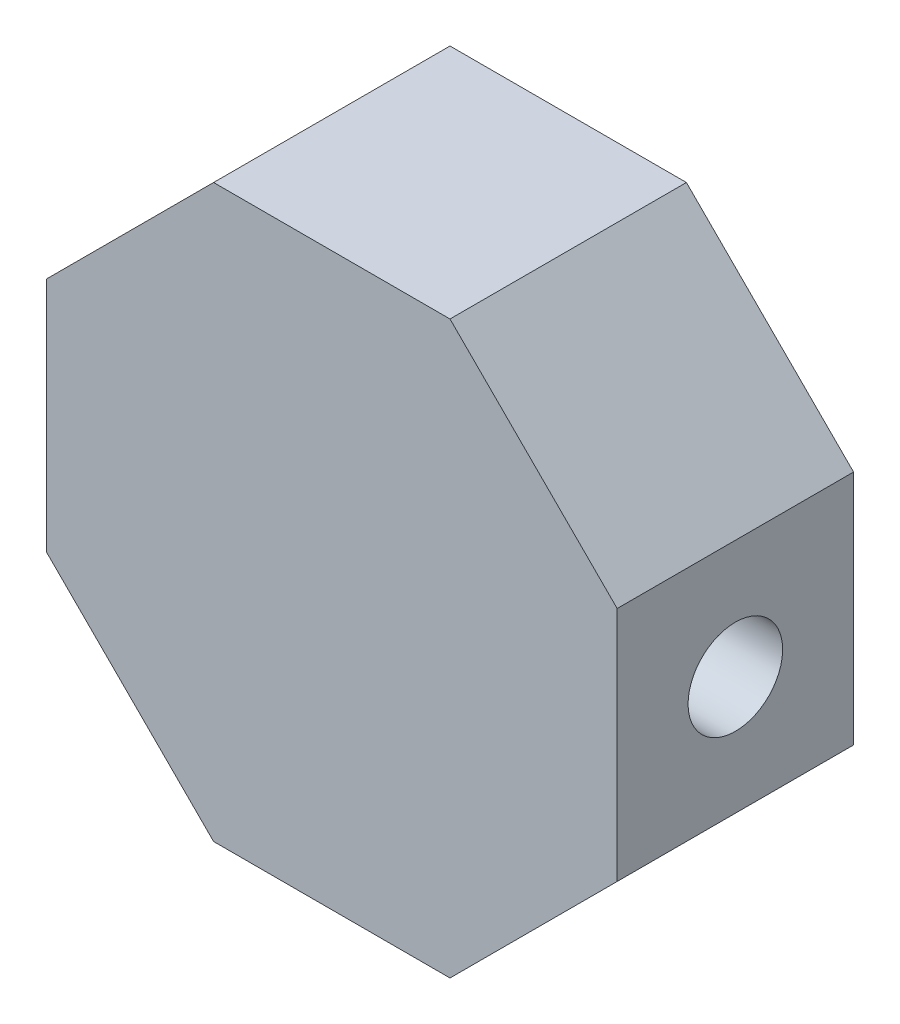
SolidWorks part; units mm, degrees
ref_plane "Front Plane" through (0, 0, 0) normal (0, 0, 1) x (1, 0, 0)
ref_plane "Top Plane" through (0, 0, 0) normal (0, 1, 0) x (1, 0, 0)
ref_plane "Right Plane" through (0, 0, 0) normal (1, 0, 0) x (0, 0, -1)
sketch "Sketch2" plane through (0, 0, 0) normal (0, 0, 1) x (1, 0, 0)
  line L0 (15.3303, 6.35) -> (15.3303, -6.35)
  line L1 (15.3303, -6.35) -> (6.35, -15.3303)
  line L2 (6.35, -15.3303) -> (-6.35, -15.3303)
  line L3 (-6.35, -15.3303) -> (-15.3303, -6.35)
  line L4 (-15.3303, -6.35) -> (-15.3303, 6.35)
  line L5 (-15.3303, 6.35) -> (-6.35, 15.3303)
  line L6 (-6.35, 15.3303) -> (6.35, 15.3303)
  line L7 (6.35, 15.3303) -> (15.3303, 6.35)
extrude "Boss-Extrude1" add sketch "Sketch2" along normal blind 12.7
sketch "Sketch3" plane through (15.3303, 0, 0) normal (1, 0, 0) x (0, 0, -1)
  line L0 (-12.7, 0) -> (0, 0) construction
  line L1 (-12.7, -6.35) -> (-12.7, 6.35) construction
  line L2 (0, -6.35) -> (0, 6.35) construction
  circle A0 centre (-6.35, 0) radius 2.54
  dimension "D1" = 5.08
extrude "Cut-Extrude1" cut sketch "Sketch3" against normal blind 12.7
